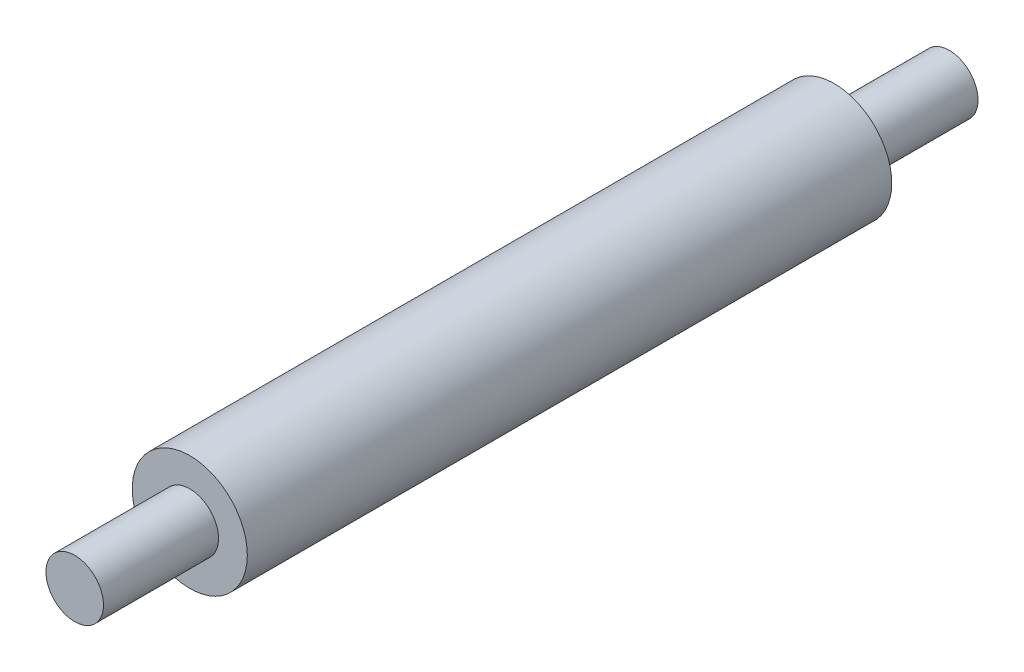
SolidWorks part; units mm, degrees
ref_plane "Front Plane" through (0, 0, 0) normal (0, 0, 1) x (1, 0, 0)
ref_plane "Top Plane" through (0, 0, 0) normal (0, 1, 0) x (1, 0, 0)
ref_plane "Right Plane" through (0, 0, 0) normal (1, 0, 0) x (0, 0, -1)
sketch "Sketch1" plane through (0, 0, 0) normal (0, 0, 1) x (1, 0, 0)
  circle A0 centre (0, 0) radius 2.5
  dimension "D1" = 5
extrude "Boss-Extrude1" add sketch "Sketch1" along normal blind 28
sketch "Sketch2" plane through (0, 0, 28) normal (0, 0, 1) x (1, 0, 0)
  circle A0 centre (0, 0) radius 1.25
  dimension "D1" = 2.5
extrude "Boss-Extrude2" add sketch "Sketch2" along normal blind 5 contours A0
sketch "Sketch3" plane through (0, 0, 0) normal (0, 0, -1) x (-1, 0, 0)
  circle A0 centre (0, 0) radius 1.25
  dimension "D1" = 2.5
extrude "Boss-Extrude3" add sketch "Sketch3" along normal blind 5
